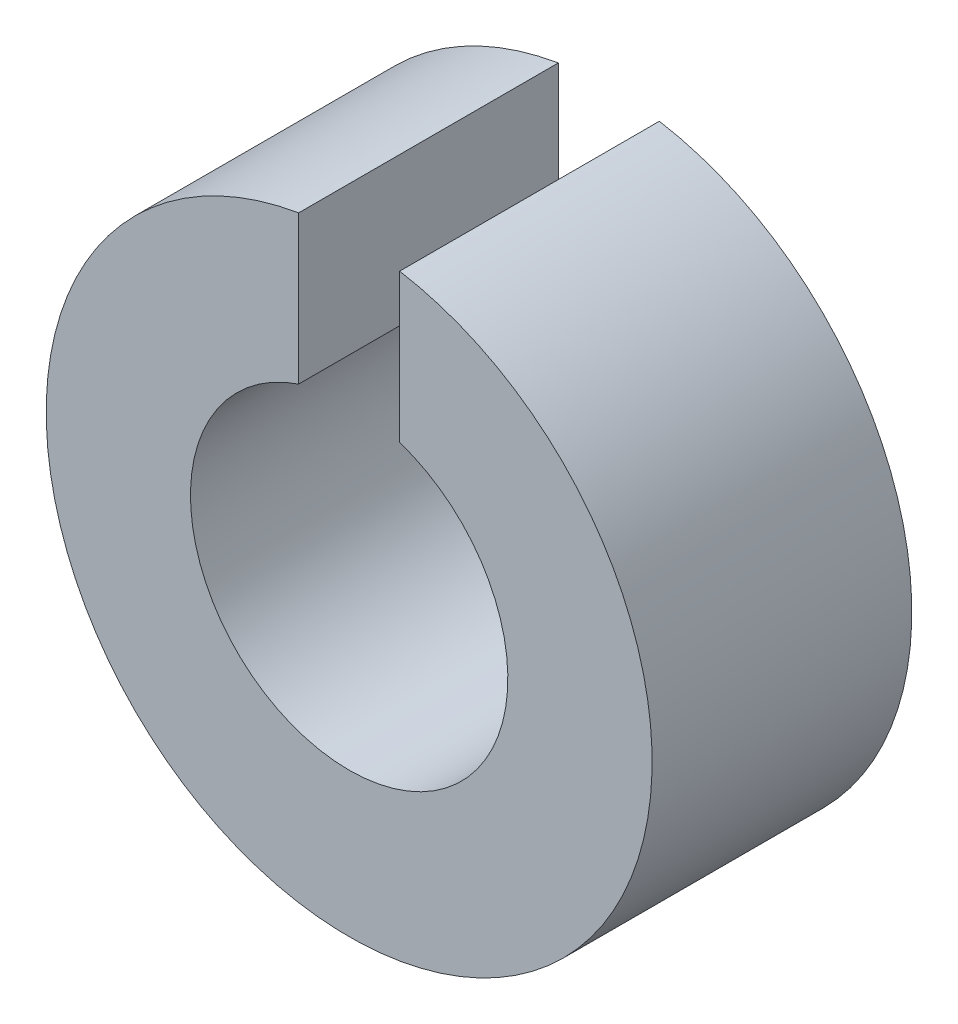
SolidWorks part; units mm, degrees
material "Фторопласт-4 ГОСТ 10007-80 Е"
ref_plane "Спереди" through (0, 0, 0) normal (0, 0, 1) x (1, 0, 0)
ref_plane "Сверху" through (0, 0, 0) normal (0, 1, 0) x (1, 0, 0)
ref_plane "Справа" through (0, 0, 0) normal (1, 0, 0) x (0, 0, -1)
sketch "Эскиз1" plane through (0, 0, 0) normal (0, 0, 1) x (1, 0, 0)
  circle A0 centre (0, 0) radius 10.5
  circle A1 centre (0, 0) radius 5.5
  dimension "D1" = 21
  dimension "D2" = 11
extrude "Бобышка-Вытянуть1" add sketch "Эскиз1" along normal blind 9
sketch "Эскиз2" plane through (0, 0, 9) normal (0, 0, 1) x (1, 0, 0)
  line L1 (-1.75, 18) -> (1.75, 18)
  line L2 (-1.75, 18) -> (-1.75, 3)
  line L3 (-1.75, 3) -> (1.75, 3)
  line L4 (1.75, 18) -> (1.75, 3)
  line L5 (-1.75, 18) -> (1.75, 3) construction
  line L6 (-1.75, 3) -> (1.75, 18) construction
  circle A0 centre (0, 0) radius 10.5 construction
  point P0 (0, 10.5)
  dimension "D1" = 3.5
  dimension "D2" = 15
extrude "Вырез-Вытянуть1" cut sketch "Эскиз2" against normal through all
